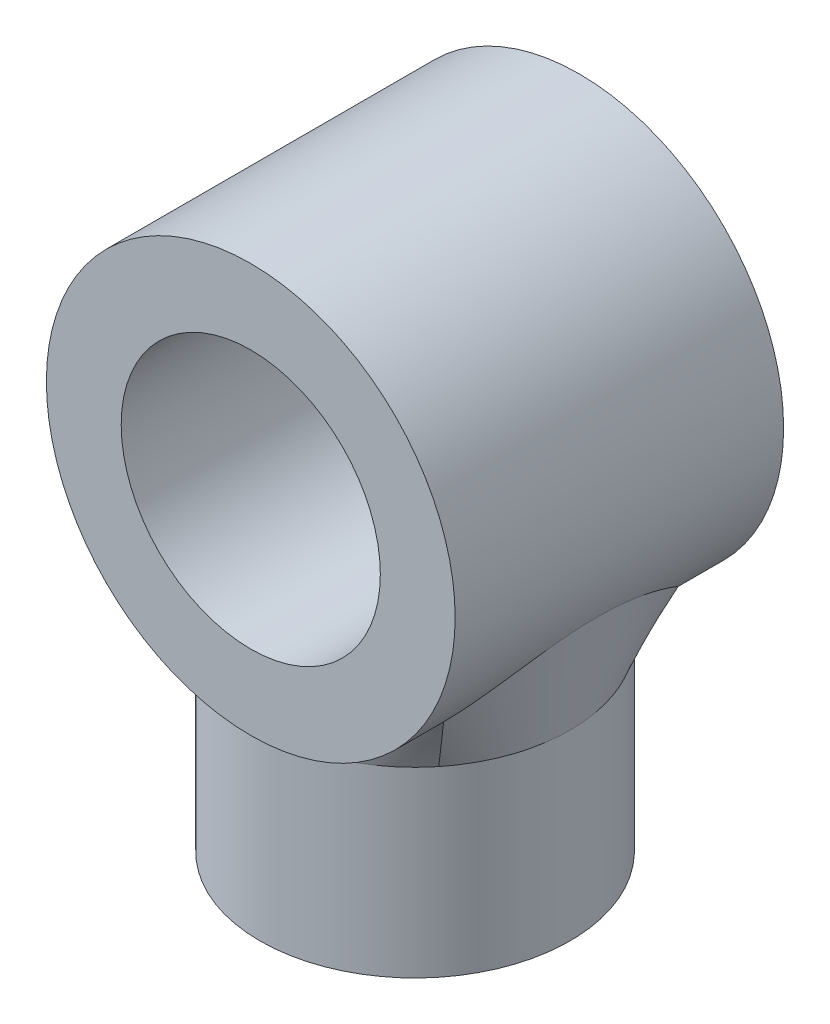
SolidWorks part; units mm, degrees
ref_plane "Front Plane" through (0, 0, 0) normal (0, 0, 1) x (1, 0, 0)
ref_plane "Top Plane" through (0, 0, 0) normal (0, 1, 0) x (1, 0, 0)
ref_plane "Right Plane" through (0, 0, 0) normal (1, 0, 0) x (0, 0, -1)
sketch "Sketch1" plane through (0, 0, 0) normal (0, 1, 0) x (1, 0, 0)
  circle A0 centre (0, 0) radius 6
  circle A1 centre (0, 0) radius 8.5
  dimension "D1" = 12
  dimension "D2" = 17
extrude "Boss-Extrude1" add sketch "Sketch1" along normal blind 10
sketch "Sketch3" plane through (0, 0, 0) normal (0, 0, 1) x (1, 0, 0)
  line L0 (8.5, 10) -> (-8.5, 10) construction
  circle A1 centre (0, 21.2) radius 11.2
  dimension "D2" = 22.4
extrude "Boss-Extrude2" add sketch "Sketch3" along normal blind 9 and the other way blind 9 separate body
ref_point "Point1"
ref_plane "Plane1" through (0, 21.2, 0) normal (0, 1, 0) x (1, 0, 0)
sketch "Sketch6" plane through (0, 10, 0) normal (0, 1, 0) x (1, 0, 0)
  circle A0 centre (0, 0) radius 8.5
  circle A1 centre (0, 0) radius 8.5 construction
sketch "Sketch7" plane through (0, 21.2, 0) normal (0, 1, 0) x (1, 0, 0)
  line L1 (-11.2, -9) -> (11.2, -9)
  line L2 (-11.2, -9) -> (-11.2, 9)
  line L3 (-11.2, 9) -> (11.2, 9)
  line L4 (11.2, -9) -> (11.2, 9)
  line L5 (-11.2, -9) -> (11.2, 9) construction
  line L6 (-11.2, 9) -> (11.2, -9) construction
  point P0 (0, 0)
loft "Loft1" add profiles "Sketch7", "Sketch6"
sketch "Sketch8" plane through (0, 0, 9) normal (0, 0, 1) x (1, 0, 0)
  line L0 (9.35, 21.2) -> (-9.35, 21.2) construction
  circle A0 centre (0, 21.2) radius 7.1
  circle A1 centre (0, 21.2) radius 11.2 construction
  dimension "D1" = 14.2
extrude "Cut-Extrude1" cut sketch "Sketch8" against normal up to surface (18 mm away) up to face at (11.2, 21.2, -9)
equation "\"pin_bore\"=14.20"
equation "\"top_outer_diameter\"=22.40"
equation "\"D2@Sketch3\"=\"top_outer_diameter\""
equation "\"D1@Sketch8\"=\"pin_bore\""
equation "\"bottom_height\"=23.10"
equation "\"bottom_bore_height\"=11.90"
